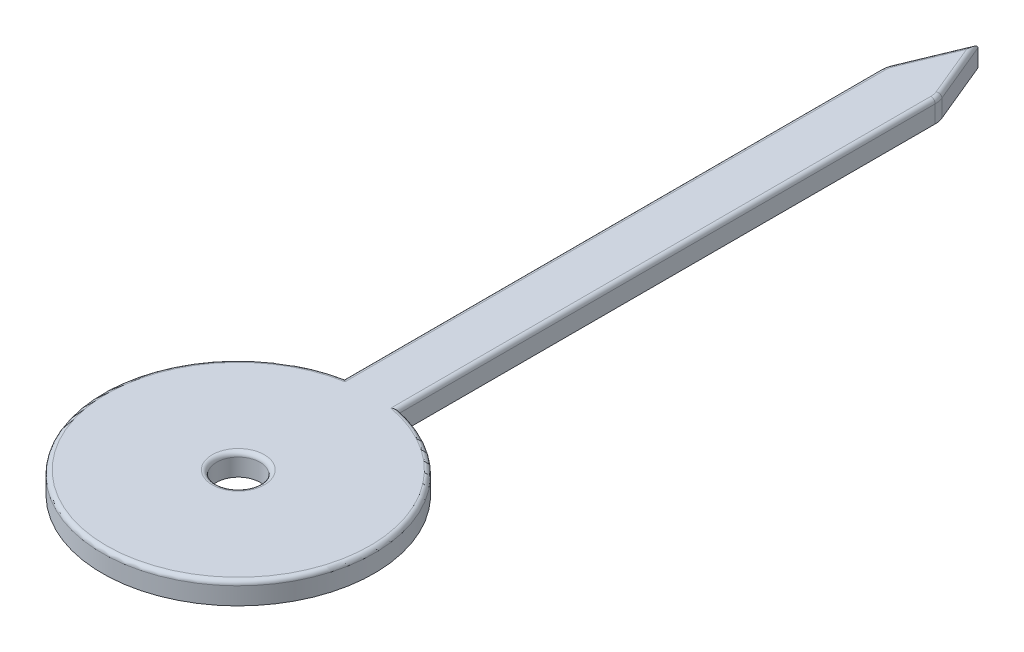
SolidWorks part; units mm, degrees
ref_plane "前视基准面" through (0, 0, 0) normal (0, 0, 1) x (1, 0, 0)
ref_plane "上视基准面" through (0, 0, 0) normal (0, 1, 0) x (1, 0, 0)
ref_plane "右视基准面" through (0, 0, 0) normal (1, 0, 0) x (0, 0, -1)
sketch "草图1" plane through (0, 0, 0) normal (0, 1, 0) x (1, 0, 0)
  line L0 (0, 0) -> (0, 3.4) construction
  line L1 (-0.125, 3.0982) -> (0, 3.4)
  line L2 (-0.125, 0.6124) -> (-0.125, 3.0982)
  line L3 (0.125, 3.0982) -> (0, 3.4)
  line L4 (0.125, 0.6124) -> (0.125, 3.0982)
  arc A0 (-0.125, 0.6124) -> (0.125, 0.6124) centre (0, 0) ccw
  circle A1 centre (0, 0) radius 0.1
  dimension "D1" = 1.25
  dimension "D5" = 0.2
  dimension "D2" = 3.4
  dimension "D3" = 0.125
  dimension "D4" = 45
extrude "凸台-拉伸1" add sketch "草图1" along normal blind 0.1
fillet "圆角1" radius 0.1 2 edges at (-0.125, 0.05, -3.0982) (0.125, 0.05, -3.0982)
fillet "圆角2" radius 0.02 8 edges at (0, 0.1, 0.1) (0.0587, 0.1, -3.2583) (0.1231, 0.1, -3.0978) (0.125, 0.1, -1.8454) (0, 0.1, 0.625) (-0.125, 0.1, -1.8454) (-0.1231, 0.1, -3.0978) (-0.0587, 0.1, -3.2583)
